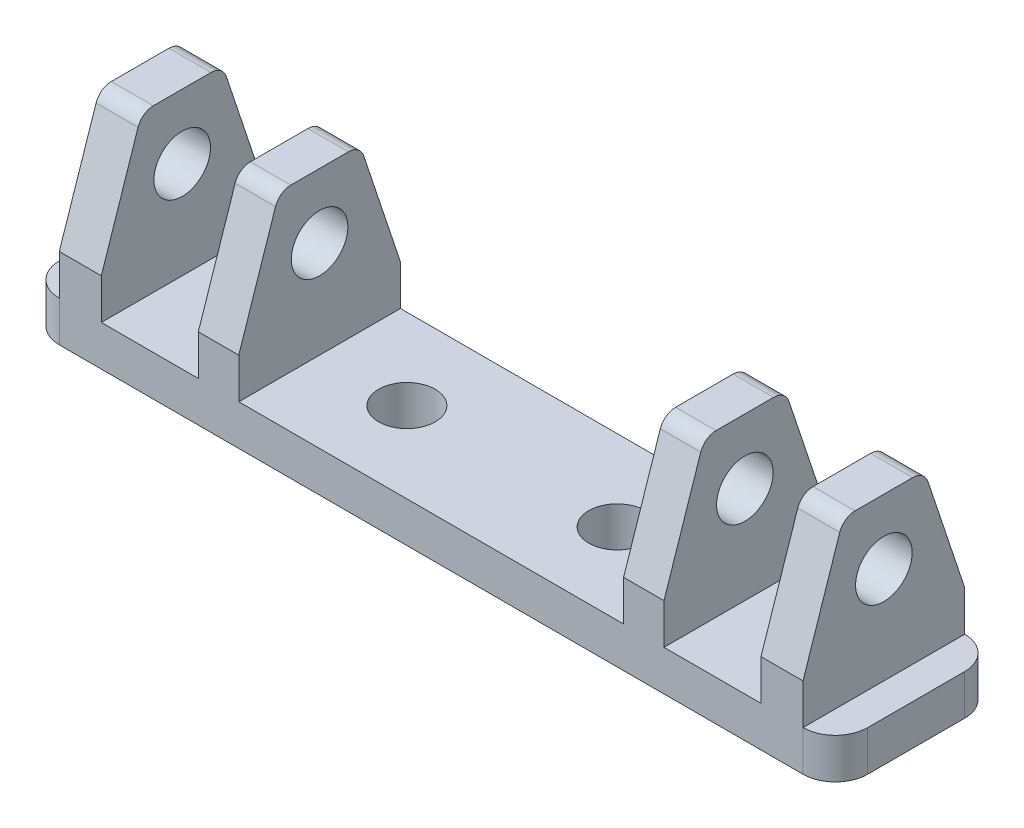
SolidWorks part; units mm, degrees
ref_plane "前视基准面" through (0, 0, 0) normal (0, 0, 1) x (1, 0, 0)
ref_plane "上视基准面" through (0, 0, 0) normal (0, 1, 0) x (1, 0, 0)
ref_plane "右视基准面" through (0, 0, 0) normal (1, 0, 0) x (0, 0, -1)
other "Configuration Table"
sketch "草图1" plane through (0, 0, 0) normal (0, 1, 0) x (1, 0, 0)
  line L1 (-23, -5) -> (23, -5)
  line L2 (-25, -3) -> (-25, 3)
  line L3 (-23, 5) -> (23, 5)
  line L4 (25, -3) -> (25, 3)
  line L5 (-25, -5) -> (25, 5) construction
  line L6 (-25, 5) -> (25, -5) construction
  arc A0 (23, -5) -> (25, -3) centre (23, -3) ccw
  arc A1 (-25, 3) -> (-23, 5) centre (-23, 3) cw
  arc A2 (-23, -5) -> (-25, -3) centre (-23, -3) cw
  arc A3 (23, 5) -> (25, 3) centre (23, 3) cw
  point P0 (0, 0)
  dimension "D3" = 2
  dimension "D1" = 10
  dimension "D2" = 50
extrude "凸台-拉伸1" add sketch "草图1" along normal blind 2.5
sketch "草图3" plane through (0, 2.5, 0) normal (0, 1, 0) x (1, 0, 0)
  line L0 (-20.4008, 5) -> (-20.4008, -5)
  line L2 (-23, -5) -> (23, -5) construction
  line L3 (-14.4008, 5) -> (-14.4008, -5)
  line L8 (0, 0) -> (0, 50000) construction
  line L9 (-20.4008, 5) -> (-23, 5)
  line L10 (-20.4008, 5) -> (-20.4008, -5)
  line L11 (-20.4008, -5) -> (-23, -5)
  line L12 (-23, 5) -> (-23, -5)
  line L13 (-14.4008, 5) -> (-11.9008, 5)
  line L14 (-14.4008, 5) -> (-14.4008, -5)
  line L15 (-14.4008, -5) -> (-11.9008, -5)
  line L16 (-11.9008, 5) -> (-11.9008, -5)
  line L17 (11.9008, 5) -> (11.9008, -5)
  line L18 (14.4008, -5) -> (11.9008, -5)
  line L19 (14.4008, 5) -> (14.4008, -5)
  line L20 (14.4008, 5) -> (11.9008, 5)
  line L21 (23, 5) -> (23, -5)
  line L22 (20.4008, -5) -> (23, -5)
  line L23 (20.4008, 5) -> (20.4008, -5)
  line L24 (20.4008, 5) -> (23, 5)
  line L25 (14.4008, 5) -> (14.4008, -5)
  line L26 (20.4008, 5) -> (20.4008, -5)
  line M6 (23, 5) -> (-23, 5)
  line M10 (-23, -5) -> (23, -5)
  dimension "D1" = 2.5
extrude "凸台-拉伸2" add sketch "草图3" along normal blind 10 contours L12 L0 M6 M10 | L16 L3 M6 M10 | L19 L17 M6 M10 | L23 L21 M6 M10
sketch "草图4" plane through (-23, 0, 0) normal (-1, 0, 0) x (0, 0, 1)
  line L0 (0, 0) -> (0, 50000) construction
  line L1 (-5, 12.5) -> (5, 12.5) construction
  line L2 (-2.5, 12.5) -> (-5, 5)
  line L3 (-5, 12.5) -> (-5, 2.5) construction
  line L4 (-5, 5) -> (-5, 12.5)
  line L5 (-5, 12.5) -> (-2.5, 12.5)
  line L6 (5, 5) -> (5, 12.5)
  line L7 (2.5, 12.5) -> (5, 5)
  line L8 (5, 12.5) -> (2.5, 12.5)
  point P5 (0, 12.5)
  dimension "D1" = 2.5
  dimension "D2" = 7.5
extrude "切除-拉伸1" cut sketch "草图4" against normal blind 59
sketch "草图5" plane through (-23, 0, 0) normal (-1, 0, 0) x (0, 0, 1)
  line L0 (-2.5, 12.5) -> (2.5, 12.5) construction
  circle A0 centre (0, 8.5) radius 1.75
  dimension "D1" = 3.5
  dimension "D2" = 4
extrude "切除-拉伸2" cut sketch "草图5" against normal blind 59
fillet "圆角1" radius 1 8 edges at (21.7004, 12.5, 2.5) (21.7004, 12.5, -2.5) (13.1508, 12.5, 2.5) (13.1508, 12.5, -2.5) (-13.1508, 12.5, -2.5) (-21.7004, 12.5, -2.5) (-21.7004, 12.5, 2.5) (-13.1508, 12.5, 2.5)
sketch "草图6" plane through (0, 2.5, 0) normal (0, 1, 0) x (1, 0, 0)
  circle A0 centre (-6.5, 0) radius 1.75
  circle A1 centre (6.5, 0) radius 1.75
  dimension "D1" = 3.5
  dimension "D2" = 3.5
  dimension "D4" = 6.5
  dimension "D3" = 6.5
extrude "切除-拉伸3" cut sketch "草图6" against normal blind 59
